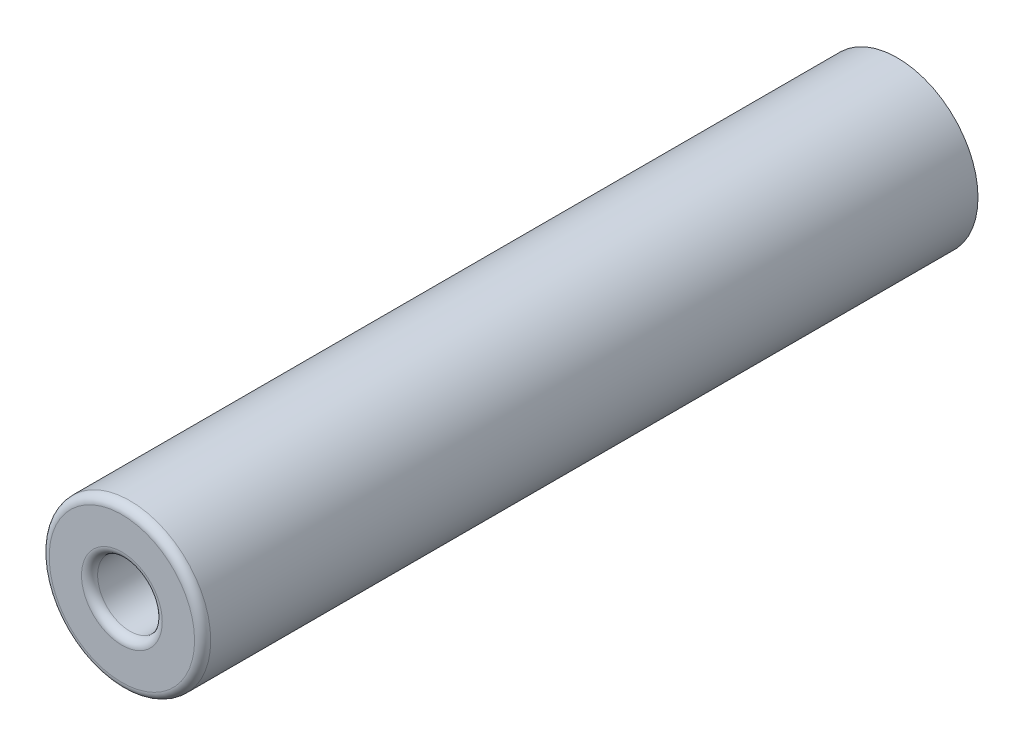
SolidWorks part; units mm, degrees
material "Acero aleado"
ref_plane "Alzado" through (0, 0, 0) normal (0, 0, 1) x (1, 0, 0)
ref_plane "Planta" through (0, 0, 0) normal (0, 1, 0) x (1, 0, 0)
ref_plane "Vista lateral" through (0, 0, 0) normal (1, 0, 0) x (0, 0, -1)
sketch "Croquis1" plane through (0, 0, 0) normal (0, 0, 1) x (1, 0, 0)
  circle A0 centre (0, 0) radius 2.5
  dimension "D1" = 5
extrude "Saliente-Extruir1" add sketch "Croquis1" along normal blind 24
sketch "Croquis2" plane through (0, 0, 24) normal (0, 0, 1) x (1, 0, 0)
  circle A0 centre (0, 0) radius 1
  dimension "D1" = 2
extrude "Cortar-Extruir1" cut sketch "Croquis2" against normal blind 10
fillet "Redondeo1" radius 0.25 2 edges at (2.5, 0, 24) (1, 0, 24)
sketch "Sketch1" plane through (0, 0, 24) normal (0, 0, 1) x (1, 0, 0)
  line L0 (0, 0) -> (0, 24.5) construction
  dimension "D1" = 24.5
